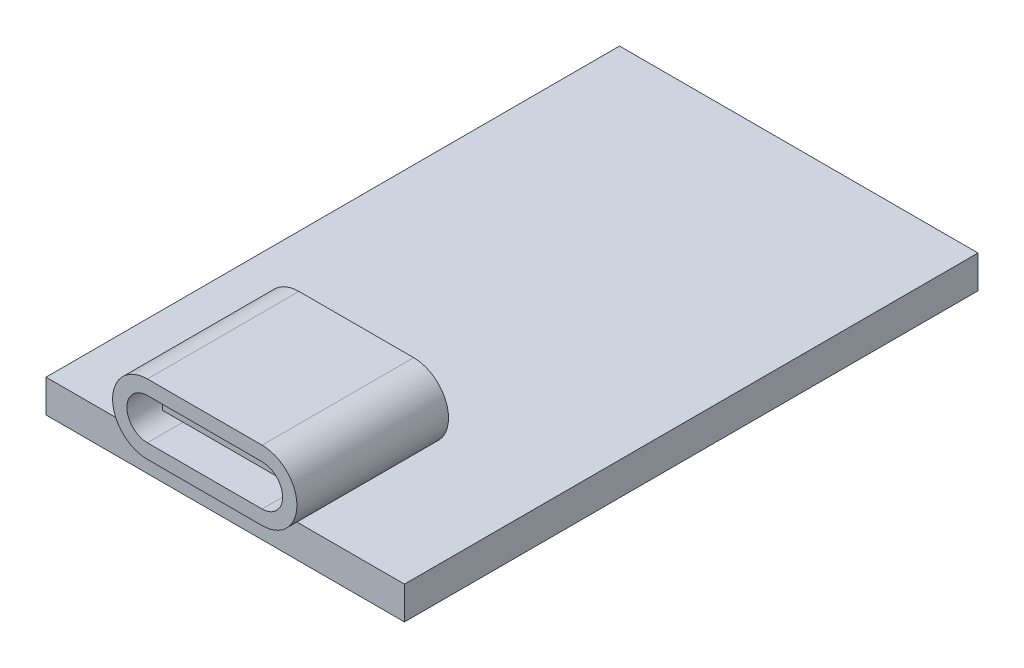
SolidWorks part; units mm, degrees
ref_plane "Front Plane" through (0, 0, 0) normal (0, 0, 1) x (1, 0, 0)
ref_plane "Top Plane" through (0, 0, 0) normal (0, 1, 0) x (1, 0, 0)
ref_plane "Right Plane" through (0, 0, 0) normal (1, 0, 0) x (0, 0, -1)
sketch "Sketch1" plane through (0, 0, 0) normal (0, 1, 0) x (1, 0, 0)
  line L1 (0, 0) -> (17.5, 0)
  line L2 (0, 0) -> (0, 28)
  line L3 (0, 28) -> (17.5, 28)
  line L4 (17.5, 0) -> (17.5, 28)
  dimension "D1" = 17.5
  dimension "D2" = 28
extrude "Boss-Extrude1" add sketch "Sketch1" along normal blind 1.6
sketch "Sketch2" plane through (0, 0, 0) normal (0, 0, 1) x (1, 0, 0)
  line L0 (5.95, 3.3) -> (11.55, 3.3) construction
  line L1 (5.95, 5) -> (11.55, 5)
  line L2 (5.95, 1.6) -> (11.55, 1.6)
  line L3 (0, 1.6) -> (17.5, 1.6) construction
  line L4 (17.5, 1.6) -> (17.5, 0) construction
  arc A0 (5.95, 5) -> (5.95, 1.6) centre (5.95, 3.3) ccw
  arc A1 (11.55, 1.6) -> (11.55, 5) centre (11.55, 3.3) ccw
  point P2 (8.75, 3.3)
  dimension "D2" = 9
  dimension "D1" = 3.4
  dimension "D3" = 8.75
extrude "Boss-Extrude2" add sketch "Sketch2" along normal blind 1 and the other way blind 6.4
sketch "Sketch3" plane through (0, 0, 1) normal (0, 0, 1) x (1, 0, 0)
  line L0 (11.55, 3.3) -> (5.95, 3.3) construction
  line L1 (11.55, 2.3) -> (5.95, 2.3)
  line L2 (11.55, 4.3) -> (5.95, 4.3)
  arc A0 (11.55, 2.3) -> (11.55, 4.3) centre (11.55, 3.3) ccw
  arc A1 (5.95, 4.3) -> (5.95, 2.3) centre (5.95, 3.3) ccw
  arc A2 (5.95, 5) -> (5.95, 1.6) centre (5.95, 3.3) ccw construction
  arc A3 (11.55, 1.6) -> (11.55, 5) centre (11.55, 3.3) ccw construction
  point P3 (8.75, 3.3)
  dimension "D1" = 1
extrude "Cut-Extrude1" cut sketch "Sketch3" against normal blind 6
sketch "Sketch4" plane through (0, 0, -5) normal (0, 0, 1) x (1, 0, 0)
  line L1 (5.6953, 3.5302) -> (11.8053, 3.5302)
  line L2 (5.6953, 3.5302) -> (5.6953, 3.0414)
  line L3 (5.6953, 3.0414) -> (11.8053, 3.0414)
  line L4 (11.8053, 3.5302) -> (11.8053, 3.0414)
extrude "Boss-Extrude3" add sketch "Sketch4" along normal blind 5
